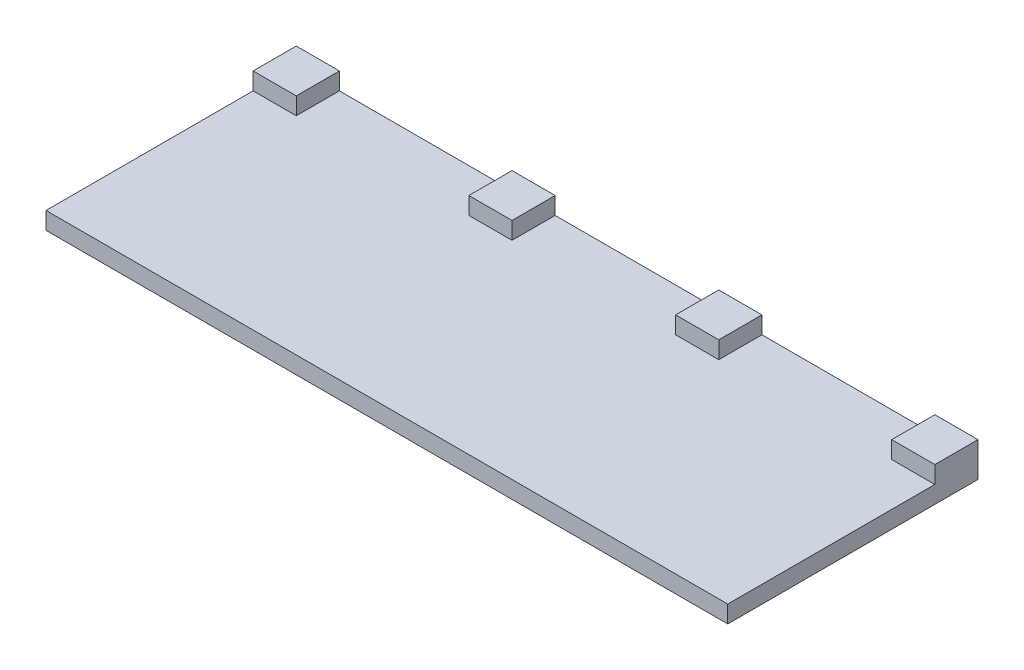
SolidWorks part; units mm, degrees
ref_plane "前视基准面" through (0, 0, 0) normal (0, 0, 1) x (1, 0, 0)
ref_plane "上视基准面" through (0, 0, 0) normal (0, 1, 0) x (1, 0, 0)
ref_plane "右视基准面" through (0, 0, 0) normal (1, 0, 0) x (0, 0, -1)
sketch "草图1" plane through (0, 0, 0) normal (0, 1, 0) x (1, 0, 0)
  line L0 (-18.4637, 26.8091) -> (-97.4637, 26.8091)
  line L1 (-97.4637, 26.8091) -> (-97.4637, -2.1909)
  line L2 (-97.4637, -2.1909) -> (-18.4637, -2.1909)
  line L3 (-18.4637, -2.1909) -> (-18.4637, 26.8091)
extrude "凸台-拉伸1" add sketch "草图1" along normal blind 2
sketch "草图2" plane through (0, 0, 0) normal (0, 1, 0) x (1, 0, 0)
  line L0 (-18.4637, 26.8091) -> (-97.4637, 26.8091) construction
  line L1 (-97.4637, 26.8091) -> (-92.4637, 26.8091)
  line L2 (-97.4637, 26.8091) -> (-97.4637, 21.8091)
  line L3 (-97.4637, 21.8091) -> (-92.4637, 21.8091)
  line L4 (-92.4637, 26.8091) -> (-92.4637, 21.8091)
  line L5 (-18.4637, -2.1909) -> (-18.4637, 26.8091) construction
  line L6 (-23.4637, 26.8091) -> (-18.4637, 26.8091)
  line L7 (-23.4637, 26.8091) -> (-23.4637, 21.8091)
  line L8 (-23.4637, 21.8091) -> (-18.4637, 21.8091)
  line L9 (-18.4637, 26.8091) -> (-18.4637, 21.8091)
extrude "凸台-拉伸3" add sketch "草图2" along normal blind 4 contours L2 L1 L4 L3 | L7 L6 L9 L8
sketch "草图3" plane through (0, 0, 0) normal (0, 1, 0) x (1, 0, 0)
  line L0 (-92.4637, 26.8091) -> (-72.4637, 26.8091)
  line L1 (-23.4637, 26.8091) -> (-92.4637, 26.8091) construction
  line L2 (-23.4637, 26.8091) -> (-43.5039, 26.8091)
  line L4 (-72.4637, 26.8091) -> (-67.4637, 26.8091)
  line L5 (-72.4637, 26.8091) -> (-72.4637, 21.8091)
  line L6 (-72.4637, 21.8091) -> (-67.4637, 21.8091)
  line L7 (-67.4637, 26.8091) -> (-67.4637, 21.8091)
  line L8 (-43.5039, 26.8091) -> (-48.5039, 26.8091)
  line L9 (-43.5039, 26.8091) -> (-43.5039, 21.8091)
  line L10 (-43.5039, 21.8091) -> (-48.5039, 21.8091)
  line L11 (-48.5039, 26.8091) -> (-48.5039, 21.8091)
extrude "凸台-拉伸4" add sketch "草图3" along normal blind 4 contours L7 L4 L5 L6 | L8 L11 L10 L9
